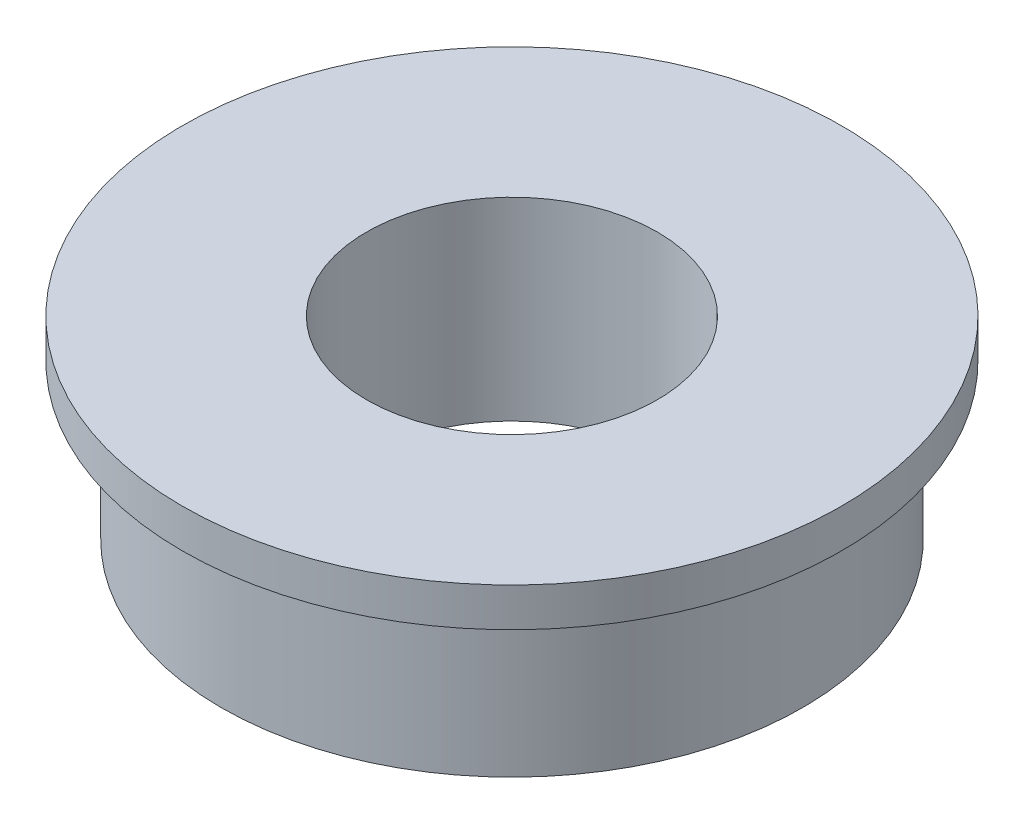
SolidWorks part; units mm, degrees
material "AISI 1045 钢，冷拔"
ref_plane "前视基准面" through (0, 0, 0) normal (0, 0, 1) x (1, 0, 0)
ref_plane "上视基准面" through (0, 0, 0) normal (0, 1, 0) x (1, 0, 0)
ref_plane "右视基准面" through (0, 0, 0) normal (1, 0, 0) x (0, 0, -1)
sketch "草图1" plane through (0, 0, 0) normal (0, 1, 0) x (1, 0, 0)
  circle A0 centre (0, 0) radius 3
  circle A1 centre (0, 0) radius 6
  dimension "D1" = 6
  dimension "D2" = 12
extrude "凸台-拉伸1" add sketch "草图1" along normal blind 3.2
sketch "草图2" plane through (0, 3.2, 0) normal (0, 1, 0) x (1, 0, 0)
  circle A1 centre (0, 0) radius 6.8
  circle A2 centre (0, 0) radius 3
  dimension "D1" = 13.6
extrude "凸台-拉伸2" add sketch "草图2" along normal blind 0.8
